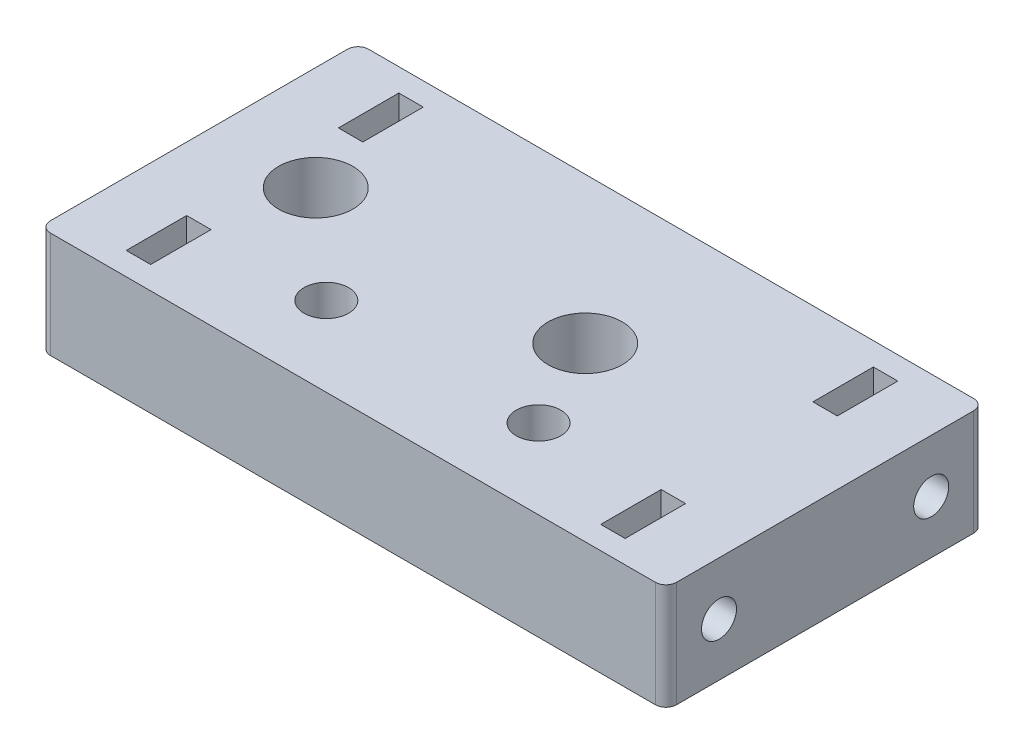
SolidWorks part; units mm, degrees
ref_plane "Front Plane" through (0, 0, 0) normal (0, 0, 1) x (1, 0, 0)
ref_plane "Top Plane" through (0, 0, 0) normal (0, 1, 0) x (1, 0, 0)
ref_plane "Right Plane" through (0, 0, 0) normal (1, 0, 0) x (0, 0, -1)
sketch "Sketch1" plane through (0, 0, 0) normal (0, 1, 0) x (1, 0, 0)
  line L1 (-29.5136, -15) -> (29.5136, -15)
  line L2 (-29.5136, -15) -> (-29.5136, 15)
  line L3 (-29.5136, 15) -> (29.5136, 15)
  line L4 (29.5136, -15) -> (29.5136, 15)
  line L5 (-29.5136, -15) -> (29.5136, 15) construction
  line L6 (-29.5136, 15) -> (29.5136, -15) construction
  point P0 (0, 0)
  dimension "D1" = 59.0272
  dimension "D2" = 30
extrude "Boss-Extrude1" add sketch "Sketch1" along normal blind 10
sketch "Sketch2" plane through (0, 10, 0) normal (0, 1, 0) x (1, 0, 0)
  line L0 (-10, -7.5) -> (10, -7.5) construction
  line L3 (0, 15) -> (0, -15) construction
  line L4 (29.5136, 15) -> (-29.5136, 15) construction
  line L5 (-29.5136, -15) -> (29.5136, -15) construction
  circle A0 centre (-10, -7.5) radius 2.1
  circle A1 centre (10, -7.5) radius 2.1
  point P3 (0, -7.5)
  dimension "D1" = 4.2
  dimension "D2" = 20
  dimension "D3" = 7.5
extrude "Cut-Extrude1" cut sketch "Sketch2" against normal through all
sketch "Sketch3" plane through (29.5136, 0, 0) normal (1, 0, 0) x (0, 0, -1)
  line L0 (0, 10) -> (0, 0) construction
  line L1 (-15, 10) -> (15, 10) construction
  line L2 (-15, 0) -> (15, 0) construction
  line L3 (-10, 5) -> (10, 5) construction
  circle A0 centre (-10, 5) radius 1.65
  circle A1 centre (10, 5) radius 1.65
  point P9 (0, 5)
  dimension "D2" = 3.3
  dimension "D1" = 20
extrude "Cut-Extrude2" cut sketch "Sketch3" against normal blind 12
sketch "Sketch4" plane through (-29.5136, 0, 0) normal (-1, 0, 0) x (0, 0, 1)
  line L0 (0, 10) -> (0, 0) construction
  line L3 (-10, 5) -> (10, 5) construction
  line L4 (-15, 10) -> (15, 10) construction
  circle A0 centre (-10, 5) radius 1.65
  circle A1 centre (10, 5) radius 1.65
  point P9 (0, 5)
  dimension "D2" = 3.3
  dimension "D1" = 20
extrude "Cut-Extrude3" cut sketch "Sketch4" against normal blind 12
ref_plane "Plane1" through (23.5136, 0, 0) normal (1, 0, 0) x (0, 0, -1)
ref_plane "Plane2" through (-23.5136, 0, 0) normal (-1, 0, 0) x (0, 0, 1)
sketch "Sketch5" plane through (23.5136, 0, 0) normal (1, 0, 0) x (0, 0, -1)
  line L0 (-12.85, 6.6454) -> (-12.85, 10)
  line L1 (-7.15, 6.6454) -> (-10, 8.2909) construction
  line L2 (-10, 8.2909) -> (-12.85, 6.6454) construction
  line L3 (-12.85, 6.6454) -> (-12.85, 3.3546)
  line L4 (-12.85, 3.3546) -> (-10, 1.7091)
  line L5 (-10, 1.7091) -> (-7.15, 3.3546)
  line L6 (-7.15, 3.3546) -> (-7.15, 6.6454)
  line L7 (10, 8.2909) -> (7.15, 6.6454) construction
  line L8 (7.15, 6.6454) -> (7.15, 3.3546)
  line L9 (7.15, 3.3546) -> (10, 1.7091)
  line L10 (10, 1.7091) -> (12.85, 3.3546)
  line L11 (12.85, 3.3546) -> (12.85, 6.6454)
  line L12 (12.85, 6.6454) -> (10, 8.2909) construction
  line L13 (-15, 10) -> (15, 10) construction
  line L14 (-12.85, 10) -> (-7.15, 10)
  line L15 (-7.15, 10) -> (-7.15, 6.6454)
  line L16 (7.15, 6.6454) -> (7.15, 10)
  line L17 (7.15, 10) -> (12.85, 10)
  line L18 (12.85, 10) -> (12.85, 6.6454)
  circle A0 centre (-10, 5) radius 2.85 construction
  circle A1 centre (10, 5) radius 2.85 construction
  dimension "D1" = 5.7
extrude "Cut-Extrude4" cut sketch "Sketch5" against normal blind 2.3
sketch "Sketch6" plane through (-23.5136, 0, 0) normal (-1, 0, 0) x (0, 0, 1)
  line L0 (-12.85, 6.6454) -> (-12.85, 10)
  line L1 (-7.15, 6.6454) -> (-10, 8.2909) construction
  line L2 (-10, 8.2909) -> (-12.85, 6.6454) construction
  line L3 (-12.85, 6.6454) -> (-12.85, 3.3546)
  line L4 (-12.85, 3.3546) -> (-10, 1.7091)
  line L5 (-10, 1.7091) -> (-7.15, 3.3546)
  line L6 (-7.15, 3.3546) -> (-7.15, 6.6454)
  line L7 (10, 8.2909) -> (7.15, 6.6454) construction
  line L8 (7.15, 6.6454) -> (7.15, 3.3546)
  line L9 (7.15, 3.3546) -> (10, 1.7091)
  line L10 (10, 1.7091) -> (12.85, 3.3546)
  line L11 (12.85, 3.3546) -> (12.85, 6.6454)
  line L12 (12.85, 6.6454) -> (10, 8.2909) construction
  line L14 (-12.85, 10) -> (-7.15, 10)
  line L15 (-7.15, 10) -> (-7.15, 6.6454)
  line L16 (7.15, 6.6454) -> (7.15, 10)
  line L17 (7.15, 10) -> (12.85, 10)
  line L18 (12.85, 10) -> (12.85, 6.6454)
  line L19 (-15, 10) -> (15, 10) construction
  circle A0 centre (-10, 5) radius 2.85 construction
  circle A1 centre (10, 5) radius 2.85 construction
  circle A2 centre (-10, 5) radius 1.65 construction
  circle A3 centre (-10, 5) radius 1.65 construction
  circle A5 centre (10, 5) radius 1.65 construction
  circle A6 centre (10, 5) radius 1.65 construction
  dimension "D1" = 5.7
extrude "Cut-Extrude5" cut sketch "Sketch6" against normal blind 2.3
sketch "Sketch7" plane through (0, 10, 0) normal (0, 1, 0) x (1, 0, 0)
  line L1 (-29.5136, -15) -> (29.5136, -15) construction
  line L2 (5.7, 1.2) -> (-19.7, 1.2) construction
  line L3 (-29.5136, 15) -> (-29.5136, -15) construction
  circle A0 centre (5.7, 1.2) radius 3.5
  circle A1 centre (-19.7, 1.2) radius 3.5
  dimension "D3" = 7
  dimension "D1" = 9.8136
  dimension "D2" = 16.2
  dimension "D4" = 25.4
extrude "Cut-Extrude6" cut sketch "Sketch7" against normal through all
fillet "Fillet1" radius 1 4 edges at (29.5136, 5, -15) (29.5136, 5, 15) (-29.5136, 5, -15) (-29.5136, 5, 15)
